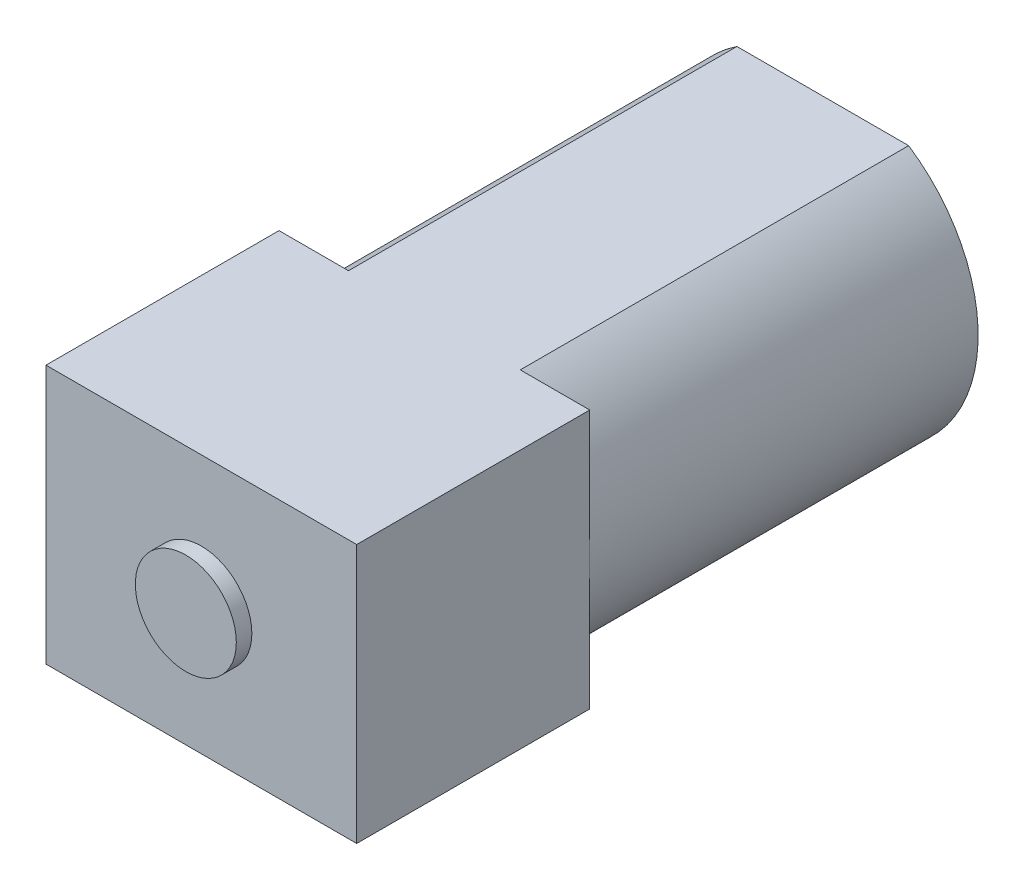
SolidWorks part; units mm, degrees
material "Plain Carbon Steel"
ref_plane "Front Plane" through (0, 0, 0) normal (0, 0, 1) x (1, 0, 0)
ref_plane "Top Plane" through (0, 0, 0) normal (0, 1, 0) x (1, 0, 0)
ref_plane "Right Plane" through (0, 0, 0) normal (1, 0, 0) x (0, 0, -1)
sketch "Sketch1" plane through (0, 0, 0) normal (0, 0, 1) x (1, 0, 0)
  line L1 (-6, 5) -> (6, 5)
  line L2 (-6, 5) -> (-6, -5)
  line L3 (-6, -5) -> (6, -5)
  line L4 (6, 5) -> (6, -5)
  dimension "D1" = 10
  dimension "D2" = 12
  dimension "D3" = 6
  dimension "D4" = 5
extrude "Boss-Extrude1" add sketch "Sketch1" along normal blind 9 and the other way blind 15
sketch "Sketch3" plane through (0, 0, -15) normal (0, 0, -1) x (-1, 0, 0)
  circle A0 centre (0, 0) radius 6
extrude "Cut-Extrude-Thin1" cut sketch "Sketch3" against normal blind 15 flip side to cut thin
sketch "Sketch5" plane through (0, 0, -15) normal (0, 0, -1) x (-1, 0, 0)
  circle A0 centre (0, 0) radius 2.5
  dimension "D1" = 5
extrude "Boss-Extrude2" add sketch "Sketch5" along normal blind 1
sketch "Sketch6" plane through (0, 0, 9) normal (0, 0, 1) x (1, 0, 0)
  circle A0 centre (0, 0) radius 1.95
  dimension "D1" = 3.9
extrude "Boss-Extrude3" add sketch "Sketch6" along normal blind 0.6
